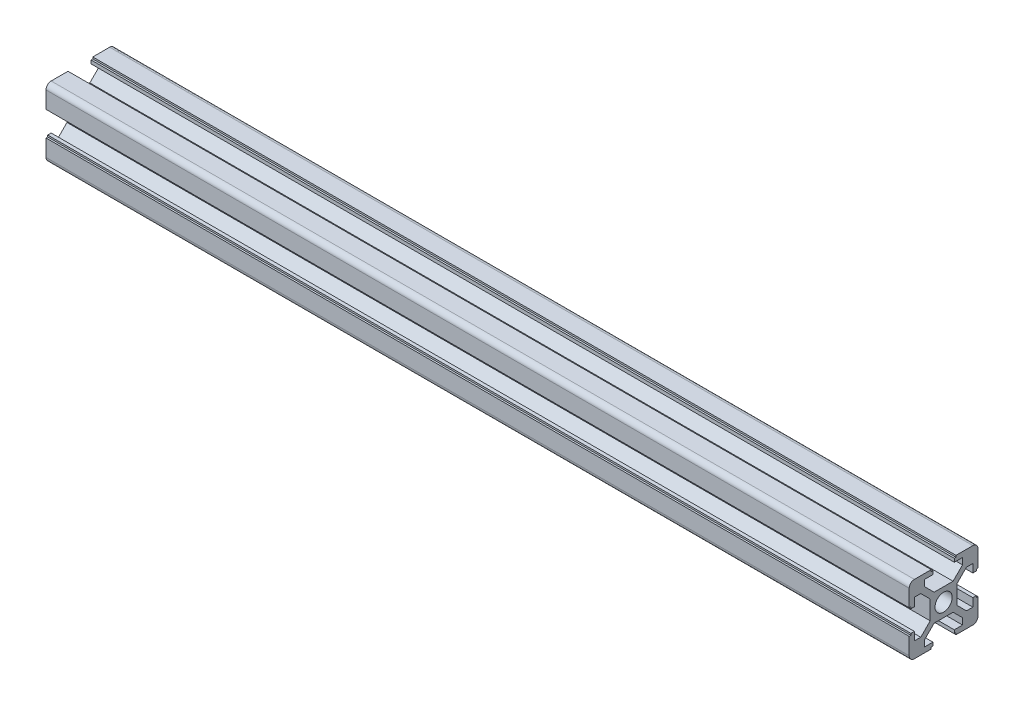
SolidWorks part; units mm, degrees
ref_plane "前视基准面" through (0, 0, 0) normal (0, 0, 1) x (1, 0, 0)
ref_plane "上视基准面" through (0, 0, 0) normal (0, 1, 0) x (1, 0, 0)
ref_plane "右视基准面" through (0, 0, 0) normal (1, 0, 0) x (0, 0, -1)
sketch "草图1" plane through (0, 0, 0) normal (0, 1, 0) x (1, 0, 0)
  line L0 (0, 0) -> (251, 0)
  dimension "D1" = 251
other "铝型材 20 X 20 X R1.5(1)"
ref_plane "基准面1" through (0, 0, 0) normal (1, 0, 0) x (0, 0, -1)
sketch "Sketch1" plane through (0, 0, 0) normal (1, 0, 0) x (0, 0, -1)
  line L0 (-3.6, 10) -> (-3.6, 9.5)
  line L1 (-3.6, 9.5) -> (-3.1, 9.5)
  line L2 (-3.1, 9.5) -> (-3.1, 8.5)
  line L3 (-3.1, 8.5) -> (-5.5, 8.5)
  line L4 (-8.5, -10) -> (-3.6, -10)
  line L5 (-10, -8.5) -> (-10, -3.6)
  line L6 (8.5, 10) -> (3.6, 10)
  line L7 (10, 8.5) -> (10, 3.6)
  line L8 (0, 14.8756) -> (0, 0) construction
  line L9 (0, 0) -> (14.1675, 0) construction
  line L10 (-5.5, 8.5) -> (-5.5, 6.65)
  line L11 (-5.5, 6.65) -> (-2.75, 3.9)
  line L12 (-2.75, 3.9) -> (2.75, 3.9)
  line L13 (5.5, 6.65) -> (2.75, 3.9)
  line L14 (5.5, 8.5) -> (5.5, 6.65)
  line L15 (3.1, 8.5) -> (5.5, 8.5)
  line L16 (3.1, 9.5) -> (3.1, 8.5)
  line L17 (3.6, 9.5) -> (3.1, 9.5)
  line L18 (3.6, 10) -> (3.6, 9.5)
  line L19 (-3.6, 10) -> (-8.5, 10)
  line L20 (10, 3.6) -> (9.5, 3.6)
  line L21 (9.5, 3.6) -> (9.5, 3.1)
  line L22 (9.5, 3.1) -> (8.5, 3.1)
  line L23 (8.5, 3.1) -> (8.5, 5.5)
  line L24 (8.5, 5.5) -> (6.65, 5.5)
  line L25 (6.65, 5.5) -> (3.9, 2.75)
  line L26 (3.9, 2.75) -> (3.9, -2.75)
  line L27 (6.65, -5.5) -> (3.9, -2.75)
  line L28 (8.5, -5.5) -> (6.65, -5.5)
  line L29 (8.5, -3.1) -> (8.5, -5.5)
  line L30 (9.5, -3.1) -> (8.5, -3.1)
  line L31 (9.5, -3.6) -> (9.5, -3.1)
  line L32 (10, -3.6) -> (9.5, -3.6)
  line L33 (3.6, -10) -> (3.6, -9.5)
  line L34 (3.6, -9.5) -> (3.1, -9.5)
  line L35 (3.1, -9.5) -> (3.1, -8.5)
  line L36 (3.1, -8.5) -> (5.5, -8.5)
  line L37 (5.5, -8.5) -> (5.5, -6.65)
  line L38 (5.5, -6.65) -> (2.75, -3.9)
  line L39 (2.75, -3.9) -> (-2.75, -3.9)
  line L40 (-5.5, -6.65) -> (-2.75, -3.9)
  line L41 (-5.5, -8.5) -> (-5.5, -6.65)
  line L42 (-3.1, -8.5) -> (-5.5, -8.5)
  line L43 (-3.1, -9.5) -> (-3.1, -8.5)
  line L44 (-3.6, -9.5) -> (-3.1, -9.5)
  line L45 (-3.6, -10) -> (-3.6, -9.5)
  line L46 (-10, -3.6) -> (-9.5, -3.6)
  line L47 (-9.5, -3.6) -> (-9.5, -3.1)
  line L48 (-9.5, -3.1) -> (-8.5, -3.1)
  line L49 (-8.5, -3.1) -> (-8.5, -5.5)
  line L50 (-8.5, -5.5) -> (-6.65, -5.5)
  line L51 (-6.65, -5.5) -> (-3.9, -2.75)
  line L52 (-3.9, -2.75) -> (-3.9, 2.75)
  line L53 (-6.65, 5.5) -> (-3.9, 2.75)
  line L54 (-8.5, 5.5) -> (-6.65, 5.5)
  line L55 (-8.5, 3.1) -> (-8.5, 5.5)
  line L56 (-9.5, 3.1) -> (-8.5, 3.1)
  line L57 (-9.5, 3.6) -> (-9.5, 3.1)
  line L58 (-10, 3.6) -> (-9.5, 3.6)
  line L59 (3.6, -10) -> (8.5, -10)
  line L60 (-10, 3.6) -> (-10, 8.5)
  line L61 (10, -3.6) -> (10, -8.5)
  circle A0 centre (0, 0) radius 2.5
  arc A1 (-10, 8.5) -> (-8.5, 10) centre (-8.5, 8.5) cw
  arc A2 (10, 8.5) -> (8.5, 10) centre (8.5, 8.5) ccw
  arc A3 (-8.5, -10) -> (-10, -8.5) centre (-8.5, -8.5) cw
  arc A4 (8.5, -10) -> (10, -8.5) centre (8.5, -8.5) ccw
  point P0 (-10, 0)
  point P1 (10, 0)
  point P2 (0, 10)
  point P3 (0, -10)
  point P4 (0, 0)
  point P5 (-10, -10)
  point P6 (10, -10)
  point P7 (10, 10)
  point P8 (-10, 10)
  point P13 (0, 0)
  point P36 (-10, 10)
  point P39 (10, 10)
  dimension "D1" = 11
  dimension "D2" = 20
  dimension "D3" = 6.2
  dimension "D4" = 7.2
  dimension "D5" = 6.1
  dimension "D6" = 5
  dimension "D7" = 1.5
  dimension "D8" = 45
  dimension "D9" = 0.5
  dimension "D10" = 1
  dimension "D11" = 5.5
